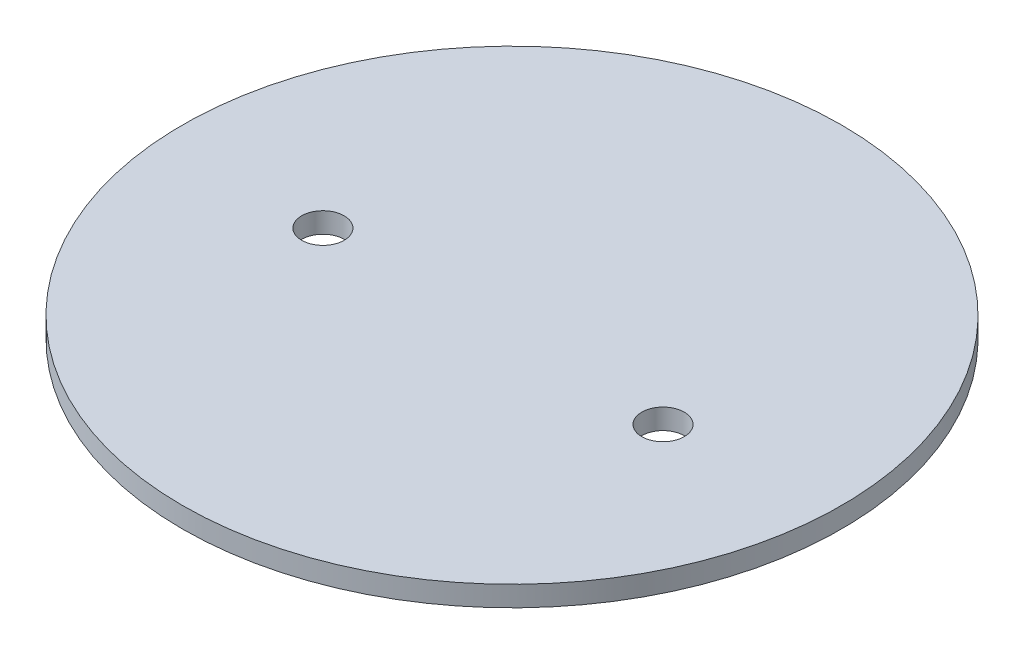
SolidWorks part; units mm, degrees
ref_plane "Front Plane" through (0, 0, 0) normal (0, 0, 1) x (1, 0, 0)
ref_plane "Top Plane" through (0, 0, 0) normal (0, 1, 0) x (1, 0, 0)
ref_plane "Right Plane" through (0, 0, 0) normal (1, 0, 0) x (0, 0, -1)
sketch "Sketch1" plane through (0, 0, 0) normal (0, 1, 0) x (1, 0, 0)
  line L0 (0, 0) -> (0, 50000) construction
  line L1 (0, -5.6) -> (-112.7727, -5.6) construction
  circle A0 centre (0, 0) radius 96.9
  circle A1 centre (-50, -5.6) radius 6.25
  circle A2 centre (50, -5.6) radius 6.25
  point P3 (0, 96.9)
  dimension "D1" = 193.8
  dimension "D3" = 12.5
  dimension "D4" = 12.5
  dimension "D2" = 102.5
  dimension "D5" = 100
  dimension "D6" = 50
extrude "Boss-Extrude1" add sketch "Sketch1" along normal mid plane 6
